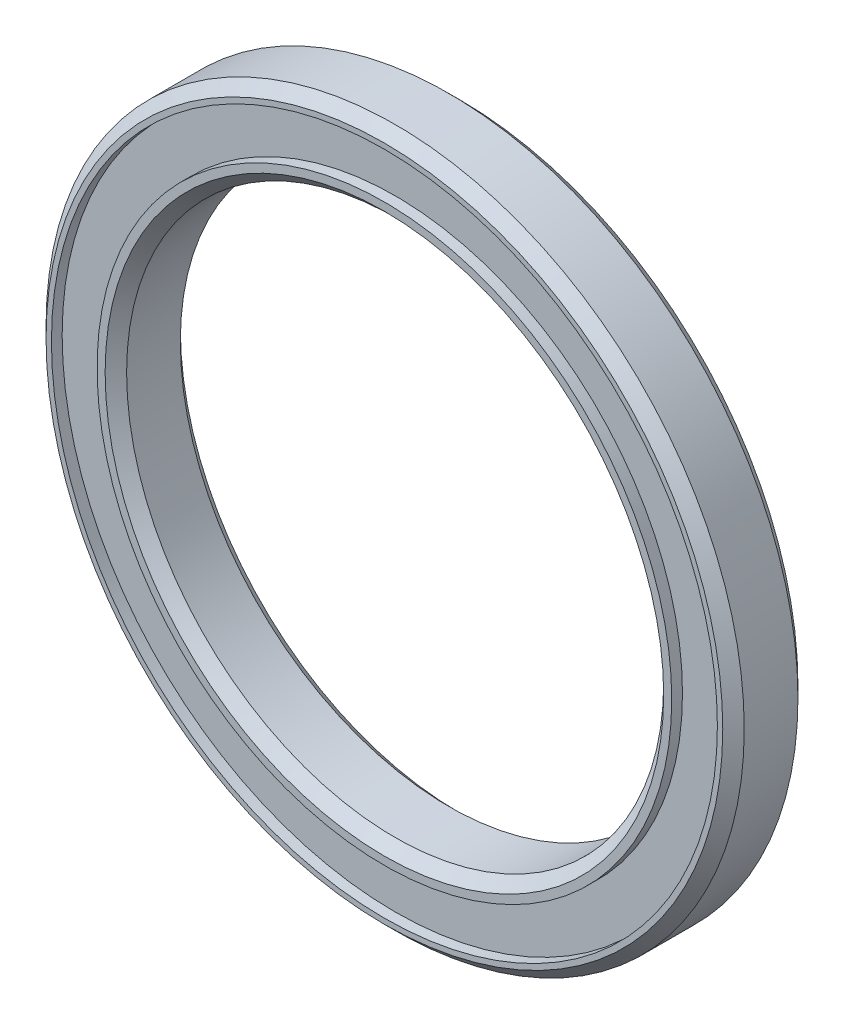
SolidWorks part; units mm, degrees
ref_plane "Front Plane" through (0, 0, 0) normal (0, 0, 1) x (1, 0, 0)
ref_plane "Top Plane" through (0, 0, 0) normal (0, 1, 0) x (1, 0, 0)
ref_plane "Right Plane" through (0, 0, 0) normal (1, 0, 0) x (0, 0, -1)
sketch "Sketch1" plane through (0, 0, 0) normal (0, 0, 1) x (1, 0, 0)
  circle A0 centre (0, 0) radius 32.5
  circle A1 centre (0, 0) radius 25
  dimension "D1" = 65
  dimension "D2" = 50
extrude "Boss-Extrude1" add sketch "Sketch1" along normal mid plane 7
sketch "Sketch2" plane through (0, 0, 3.5) normal (0, 0, 1) x (1, 0, 0)
  circle A0 centre (0, 0) radius 31
  circle A1 centre (0, 0) radius 26.75
  dimension "D1" = 53.5
  dimension "D2" = 62
extrude "Cut-Extrude1" cut sketch "Sketch2" against normal blind 1
mirror "Mirror1" about plane through (0, 0, 0) normal (0, 0, 1) of "Cut-Extrude1"
chamfer "Chamfer1" distance 1 angle 45 4 edges at (25, 0, -3.5) (25, 0, 3.5) (32.5, 0, -3.5) (32.5, 0, 3.5)
